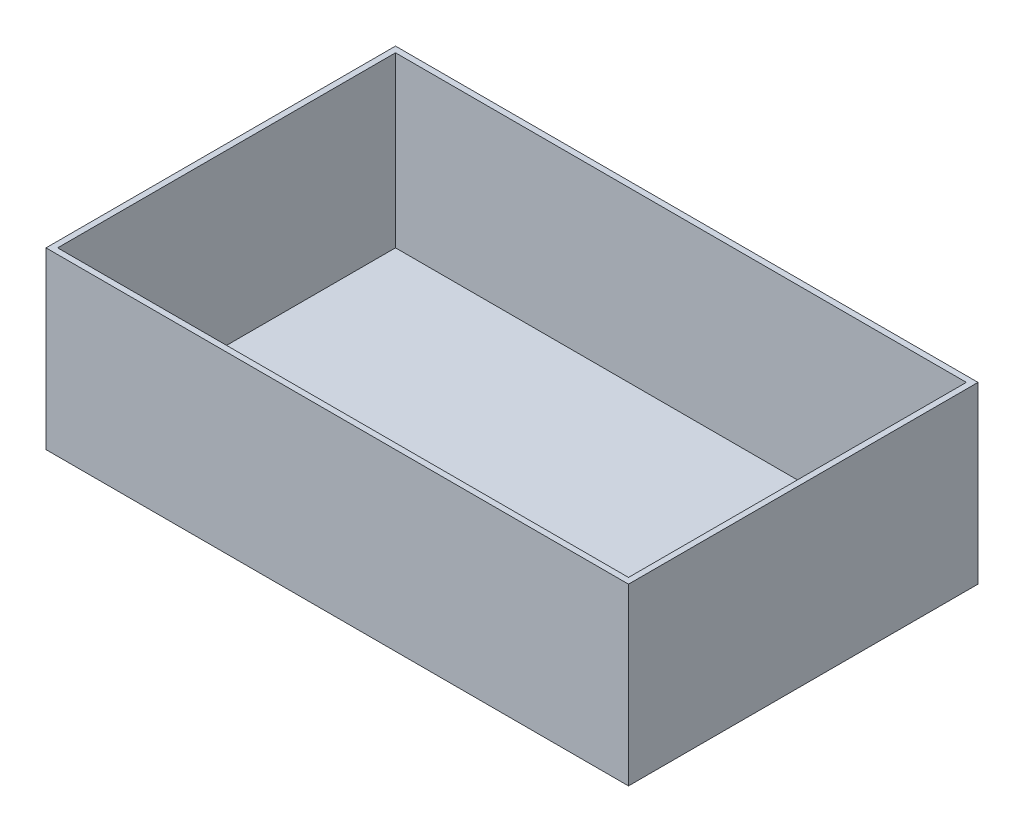
SolidWorks part; units mm, degrees
ref_plane "Front Plane" through (0, 0, 0) normal (0, 0, 1) x (1, 0, 0)
ref_plane "Top Plane" through (0, 0, 0) normal (0, 1, 0) x (1, 0, 0)
ref_plane "Right Plane" through (0, 0, 0) normal (1, 0, 0) x (0, 0, -1)
sketch "Sketch1" plane through (0, 0, 0) normal (0, 1, 0) x (1, 0, 0)
  line L1 (-250, -150) -> (250, -150)
  line L2 (-250, -150) -> (-250, 150)
  line L3 (-250, 150) -> (250, 150)
  line L4 (250, -150) -> (250, 150)
  line L5 (-250, -150) -> (250, 150) construction
  line L6 (-250, 150) -> (250, -150) construction
  point P0 (0, 0)
  dimension "D1" = 500
  dimension "D2" = 300
extrude "Boss-Extrude1" add sketch "Sketch1" along normal blind 5
sketch "Sketch2" plane through (0, 5, 0) normal (0, 1, 0) x (1, 0, 0)
  line L8 (245, -145) -> (245, 145)
  line L9 (245, 145) -> (-245, 145)
  line L10 (-245, 145) -> (-245, -145)
  line L11 (-245, -145) -> (245, -145)
  line L12 (245, -145) -> (245, 145)
  line L13 (245, 145) -> (-245, 145)
  line L14 (-245, 145) -> (-245, -145)
  line L15 (-245, -145) -> (245, -145)
  line L16 (250, -150) -> (250, 150)
  line L17 (250, 150) -> (-250, 150)
  line L18 (-250, 150) -> (-250, -150)
  line L19 (-250, -150) -> (250, -150)
  line L20 (250, -150) -> (250, 150)
  line L21 (250, 150) -> (-250, 150)
  line L22 (-250, 150) -> (-250, -150)
  line L23 (-250, -150) -> (250, -150)
  dimension "D1" = 5
  dimension "D2" = 0
extrude "Boss-Extrude2" add sketch "Sketch2" along normal blind 145
